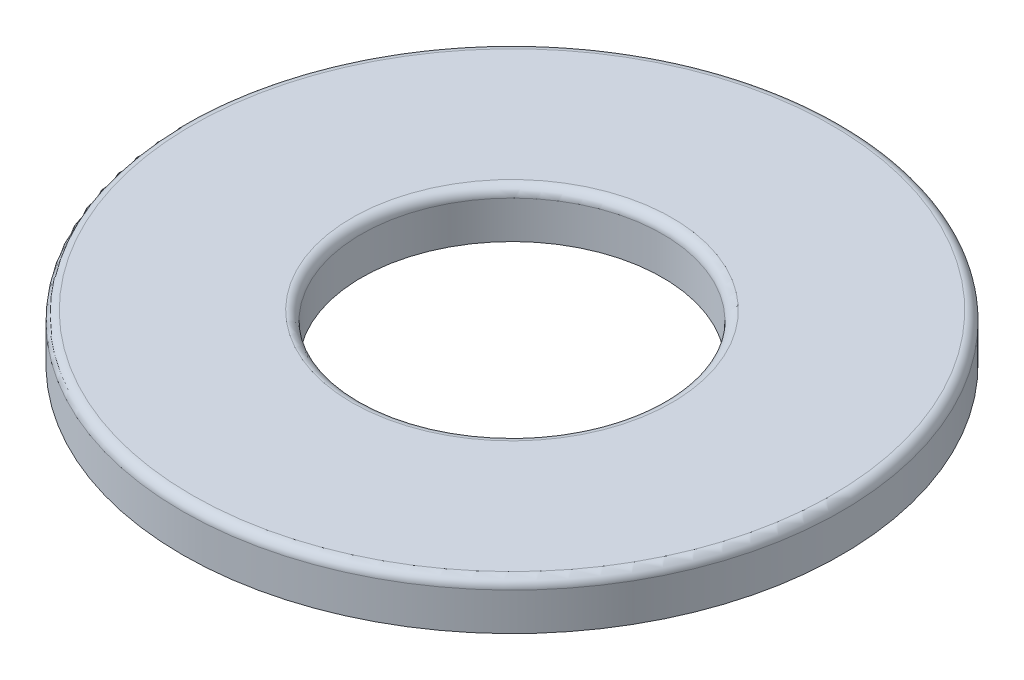
SolidWorks part; units mm, degrees
material "AISI Typ 316L stal nierdzewna"
ref_plane "Płaszczyzna przednia" through (0, 0, 0) normal (0, 0, 1) x (1, 0, 0)
ref_plane "Płaszczyzna górna" through (0, 0, 0) normal (0, 1, 0) x (1, 0, 0)
ref_plane "Płaszczyzna prawa" through (0, 0, 0) normal (1, 0, 0) x (0, 0, -1)
sketch "Szkic1" plane through (0, 0, 0) normal (0, 1, 0) x (1, 0, 0)
  circle A0 centre (0, 0) radius 3.5
  circle A1 centre (0, 0) radius 1.6
  dimension "D1" = 7
  dimension "D2" = 3.2
extrude "Dodanie-wyciągnięcie1" add sketch "Szkic1" along normal blind 0.5
fillet "Zaokrąglenie1" radius 0.1 2 edges at (0, 0.5, 1.6) (0, 0.5, 3.5)
